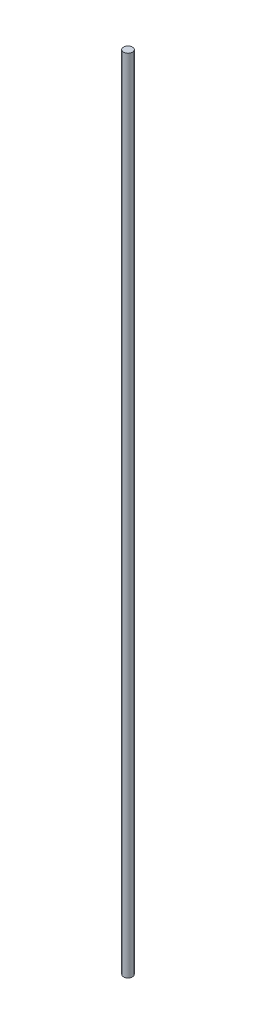
SolidWorks part; units mm, degrees
ref_plane "Front Plane" through (0, 0, 0) normal (0, 0, 1) x (1, 0, 0)
ref_plane "Top Plane" through (0, 0, 0) normal (0, 1, 0) x (1, 0, 0)
ref_plane "Right Plane" through (0, 0, 0) normal (1, 0, 0) x (0, 0, -1)
sketch "Sketch2" plane through (0, 0, 0) normal (0, 1, 0) x (1, 0, 0)
  circle A0 centre (0, 0) radius 6.35
extrude "Boss-Extrude1" add sketch "Sketch2" against normal blind 457.2 and the other way blind 685.8
